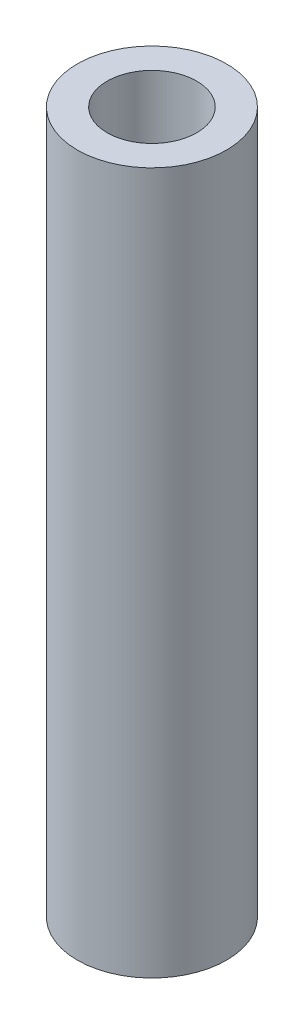
SolidWorks part; units mm, degrees
material "1060 Alloy"
ref_plane "Front Plane" through (0, 0, 0) normal (0, 0, 1) x (1, 0, 0)
ref_plane "Top Plane" through (0, 0, 0) normal (0, 1, 0) x (1, 0, 0)
ref_plane "Right Plane" through (0, 0, 0) normal (1, 0, 0) x (0, 0, -1)
sketch "Sketch1" plane through (0, 0, 0) normal (0, 1, 0) x (1, 0, 0)
  circle A0 centre (0, 0) radius 3
  circle A1 centre (0, 0) radius 5
extrude "Boss-Extrude1" add sketch "Sketch1" along normal blind 47
